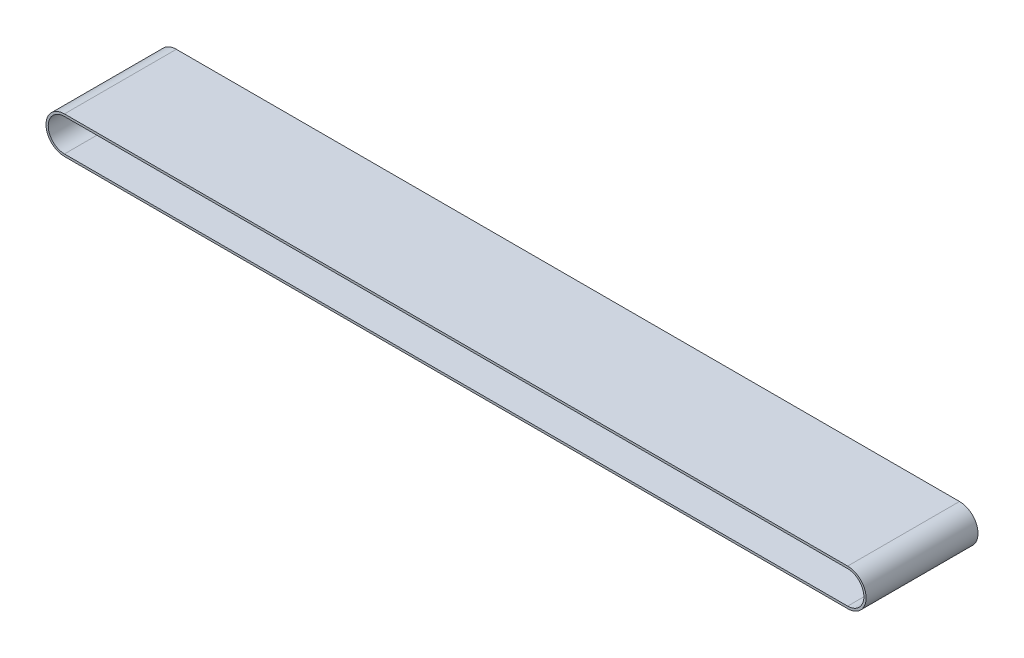
SolidWorks part; units mm, degrees
ref_plane "Front Plane" through (0, 0, 0) normal (0, 0, 1) x (1, 0, 0)
ref_plane "Top Plane" through (0, 0, 0) normal (0, 1, 0) x (1, 0, 0)
ref_plane "Right Plane" through (0, 0, 0) normal (1, 0, 0) x (0, 0, -1)
sketch "Sketch2" plane through (0, 0, 0) normal (0, 0, 1) x (1, 0, 0)
  line L0 (0, 0) -> (1, 0) construction
  line L1 (0, 0) -> (0, 1) construction
  line L2 (0, -14.5) -> (-700, -14.5)
  line L3 (-700, 14.5) -> (0, 14.5)
  arc A0 (0, 14.5) -> (0, -14.5) centre (0, 0) cw
  arc A1 (-700, -14.5) -> (-700, 14.5) centre (-700, 0) cw
extrude "Extrude-Thin1" add sketch "Sketch2" along normal mid plane 100 thin thin type one direction wall 2
